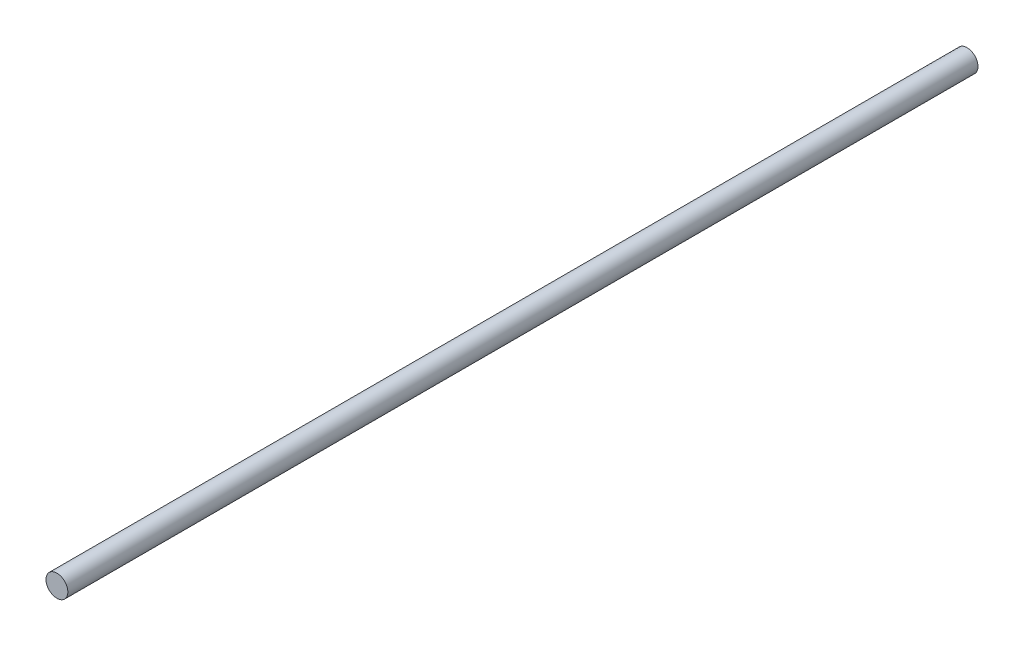
SolidWorks part; units mm, degrees
material "AISI 1020"
ref_plane "Front Plane" through (0, 0, 0) normal (0, 0, 1) x (1, 0, 0)
ref_plane "Top Plane" through (0, 0, 0) normal (0, 1, 0) x (1, 0, 0)
ref_plane "Right Plane" through (0, 0, 0) normal (1, 0, 0) x (0, 0, -1)
sketch "Sketch1" plane through (0, 0, 0) normal (0, 0, 1) x (1, 0, 0)
  circle A0 centre (0, 0) radius 6
  dimension "D1" = 12
extrude "Boss-Extrude1" add sketch "Sketch1" along normal mid plane 500
